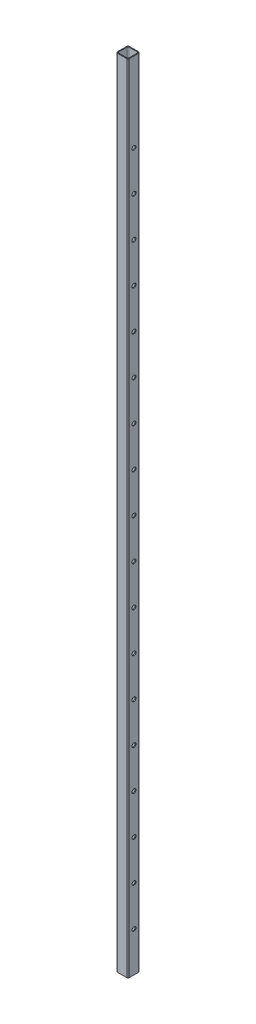
SolidWorks part; units mm, degrees
material "СТ3КП"
ref_plane "Спереди" through (0, 0, 0) normal (0, 0, 1) x (1, 0, 0)
ref_plane "Сверху" through (0, 0, 0) normal (0, 1, 0) x (1, 0, 0)
ref_plane "Справа" through (0, 0, 0) normal (1, 0, 0) x (0, 0, -1)
sketch "Эскиз1" plane through (0, 0, 0) normal (0, 1, 0) x (1, 0, 0)
  line L0 (15, 15) -> (15, -15) construction
  line L1 (-15, 15) -> (15, 15) construction
  line B0 (-12, 15) -> (12, 15)
  line B1 (-15, 12) -> (-15, -12)
  line B2 (-12, -15) -> (12, -15)
  line B3 (15, 12) -> (15, -12)
  line B4 (-11, 13) -> (11, 13)
  line B5 (-13, 11) -> (-13, -11)
  line B6 (-11, -13) -> (11, -13)
  line B7 (13, 11) -> (13, -11)
  arc B8 (-15, -12) -> (-12, -15) centre (-12, -12) ccw
  arc B9 (12, -15) -> (15, -12) centre (12, -12) ccw
  arc B10 (12, 15) -> (15, 12) centre (12, 12) cw
  arc B11 (-12, 15) -> (-15, 12) centre (-12, 12) ccw
  arc B12 (-13, -11) -> (-11, -13) centre (-11, -11) ccw
  arc B13 (11, -13) -> (13, -11) centre (11, -11) ccw
  arc B14 (11, 13) -> (13, 11) centre (11, 11) cw
  arc B15 (-11, 13) -> (-13, 11) centre (-11, 11) ccw
sketch_block_instance "Блок-30х30х2-1"
sketch_block "Блок-30х30х2" parameters "D3"=3, "D4"=2, "D1"=30, "D2"=2
extrude "Бобышка-Вытянуть1" add sketch "Эскиз1" along normal blind 2000
sketch "Эскиз2" plane through (0, 0, 0) normal (1, 0, 0) x (0, 0, -1)
  line L0 (-5, 100) -> (5, 100) construction
  line L2 (5, 0) -> (-5, 0) construction
  line L3 (0, 100) -> (0, 200) construction
  circle A0 centre (0, 100) radius 5
  circle A1 centre (0, 200) radius 5
  circle A2 centre (0, 300) radius 5
  circle A3 centre (0, 400) radius 5
  circle A4 centre (0, 500) radius 5
  circle A5 centre (0, 600) radius 5
  circle A6 centre (0, 700) radius 5
  circle A7 centre (0, 800) radius 5
  circle A8 centre (0, 900) radius 5
  circle A9 centre (0, 1000) radius 5
  circle A10 centre (0, 1100) radius 5
  circle A11 centre (0, 1200) radius 5
  circle A12 centre (0, 1300) radius 5
  circle A13 centre (0, 1400) radius 5
  circle A14 centre (0, 1500) radius 5
  circle A15 centre (0, 1600) radius 5
  circle A16 centre (0, 1700) radius 5
  circle A17 centre (0, 1800) radius 5
  dimension "D1" = 100
  dimension "D3" = 100
  dimension "D2" = 18
extrude "Вырез-Вытянуть1" cut sketch "Эскиз2" against normal through all both and the other way through all
